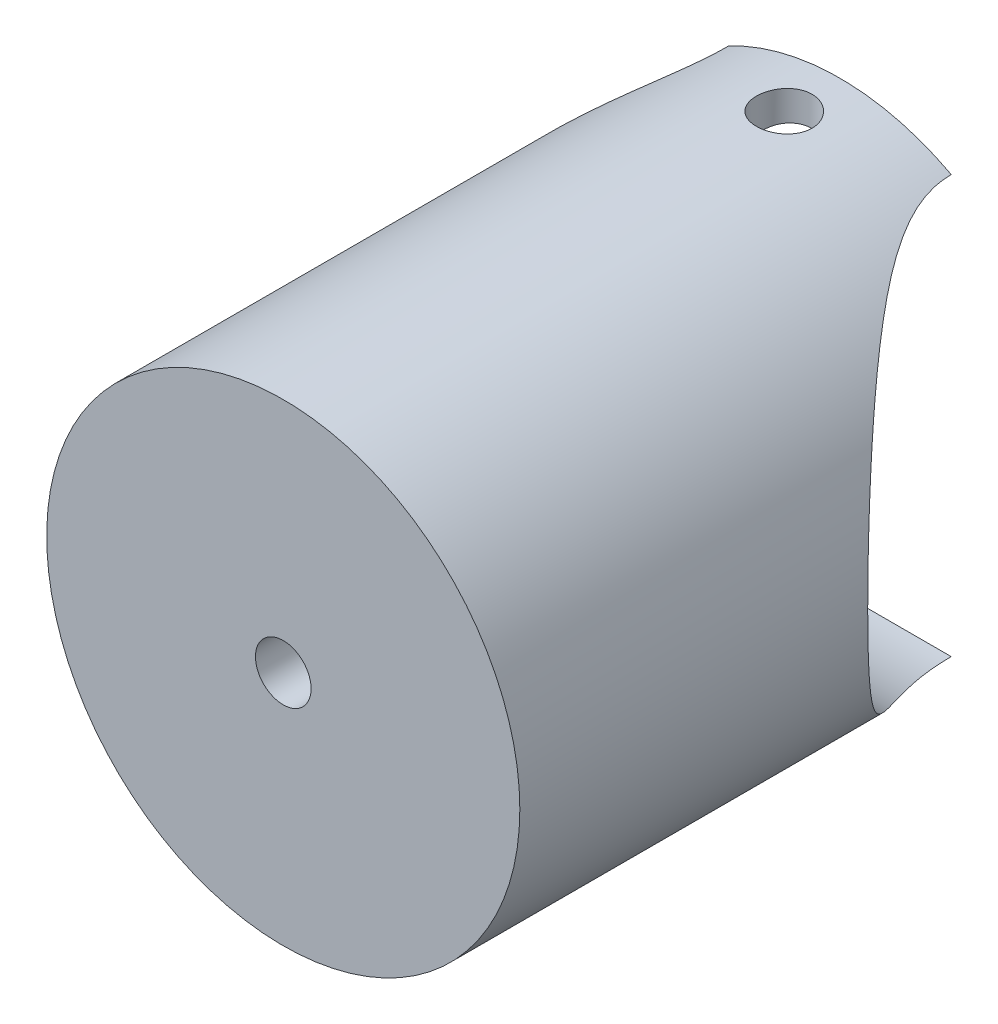
SolidWorks part; units mm, degrees
ref_plane "Front Plane" through (0, 0, 0) normal (0, 0, 1) x (1, 0, 0)
ref_plane "Top Plane" through (0, 0, 0) normal (0, 1, 0) x (1, 0, 0)
ref_plane "Right Plane" through (0, 0, 0) normal (1, 0, 0) x (0, 0, -1)
sketch "Sketch1" plane through (0, 0, 0) normal (0, 0, 1) x (1, 0, 0)
  circle A0 centre (0, 0) radius 85
  dimension "D1" = 170
extrude "Boss-Extrude1" add sketch "Sketch1" along normal blind 200
sketch "Sketch2" plane through (0, 0, 0) normal (1, 0, 0) x (0, 0, -1)
  circle A0 centre (0, 0) radius 75
  dimension "D1" = 150
extrude "Cut-Extrude1" cut sketch "Sketch2" against normal through all and the other way through all
sketch "Sketch3" plane through (0, 0, 0) normal (0, 1, 0) x (1, 0, 0)
  line L0 (0, 0) -> (0, -200) construction
  line L1 (-85, -200) -> (85, -200) construction
  circle A0 centre (0, -20) radius 10
  dimension "D1" = 20
  dimension "D2" = 20
extrude "Cut-Extrude3" cut sketch "Sketch3" against normal through all and the other way through all
sketch "Sketch4" plane through (0, 0, 0) normal (0, 0, 1) x (1, 0, 0)
  line L0 (96.735, 0) -> (-99.1362, 0) construction
  circle A0 centre (0, 0) radius 10
  dimension "D1" = 20
extrude "Cut-Extrude4" cut sketch "Sketch4" against normal through all and the other way through all
